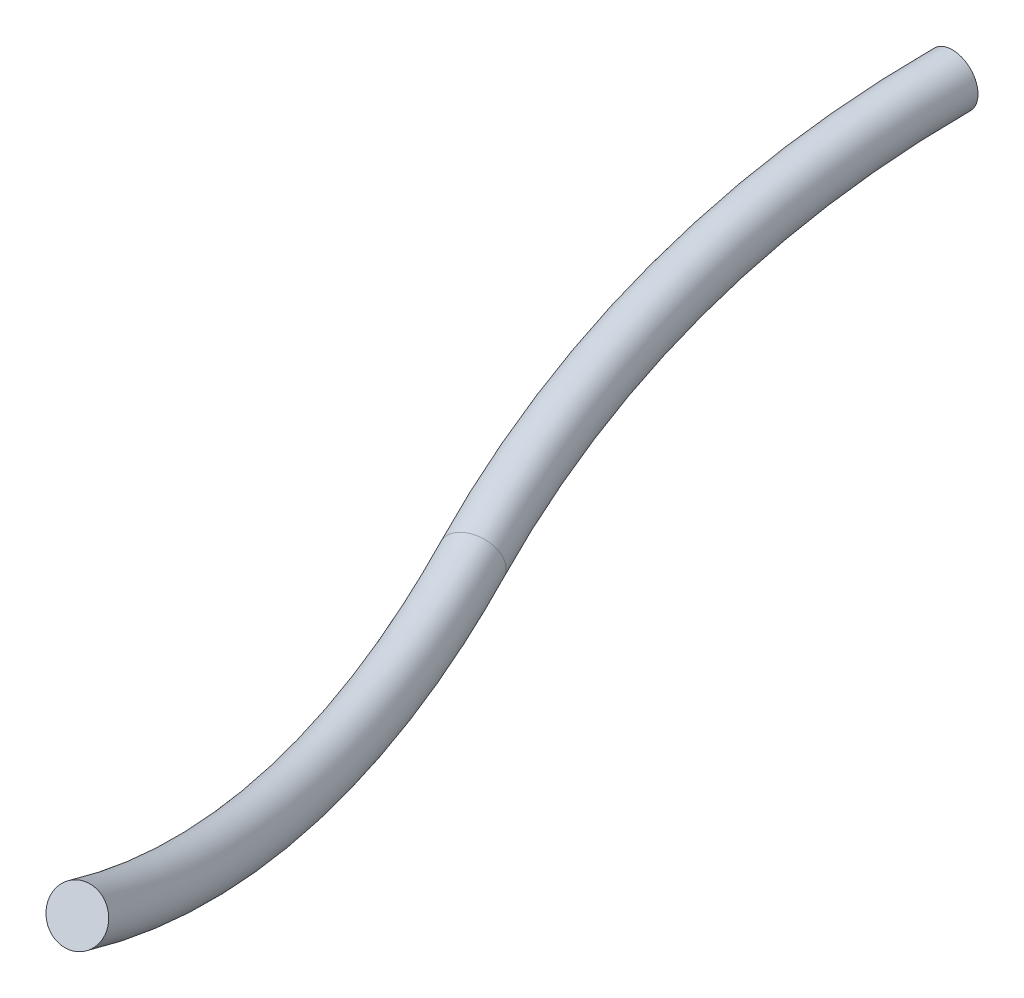
SolidWorks part; units mm, degrees
ref_plane "Front" through (0, 0, 0) normal (0, 0, 1) x (1, 0, 0)
ref_plane "Top" through (0, 0, 0) normal (0, 1, 0) x (1, 0, 0)
ref_plane "Right" through (0, 0, 0) normal (1, 0, 0) x (0, 0, -1)
sketch "Sketch2" plane through (0, 0, 0) normal (0, 0, 1) x (0.9603, -0.279, 0)
  circle A0 centre (5185.6178, -12526.2794) radius 50.8
  circle A1 centre (5185.6178, -12526.2794) radius 50.8 construction
ref_plane "Plane2" through (-5131.079, -10122.1866, 0) normal (0.4521, 0.8919, 0) x (-0.8723, 0.4422, 0.2087)
sketch "Sketch4" plane through (-5131.079, -10122.1866, 0) normal (0.4521, 0.8919, 0) x (-0.8723, 0.4422, 0.2087)
  line L0 (-7260.2099, 2757.3782) -> (-7664.802, 4558.8844) construction
  line L1 (-7253.7273, 1547.6157) -> (-6966.9992, 2891.5204) construction
  arc A0 (-7253.7273, 1547.6157) -> (-7260.2099, 2757.3782) centre (-10019.445, 2137.6941) ccw
  point P3 (-7191.481, 2140.1477)
  dimension "D1" = 1219.2
  dimension "D2" = 622.3
ref_plane "Plane3" through (-2332.401, -709.4, 809.3953) normal (-0.908, -0.2762, 0.3151) x (0.1861, 0.4079, 0.8939)
sketch "Sketch5" plane through (-2332.401, -709.4, 809.3953) normal (-0.908, -0.2762, 0.3151) x (0.1861, 0.4079, 0.8939)
  line L0 (-4168.9936, -12849.9589) -> (-2683.8344, -13946.9645) construction
  line L2 (-3031.4494, -13229.7445) -> (-649.1777, -13249.4292) construction
  arc A0 (-4168.9936, -12849.9589) -> (-3031.4494, -13229.7445) centre (-3015.4064, -11288.1977) ccw
  point P3 (-3246.7983, -13215.9734)
  point P5 (-4010.4603, -12955.4497)
  dimension "D1" = 1219.2
  dimension "D2" = 215.9
  dimension "D3" = 812.8
sweep "Sweep1" add profiles "Sketch2" path "Sketch4"
sketch "Sketch6" plane through (1595.7872, -808.927, 3889.5245) normal (0.3727, -0.1889, 0.9085) x (0.8138, 0.537, -0.2222)
  circle A0 centre (-6165.4606, -11522.0749) radius 50.8
sweep "Sweep2" add profiles "Sketch6" path "Sketch5"
